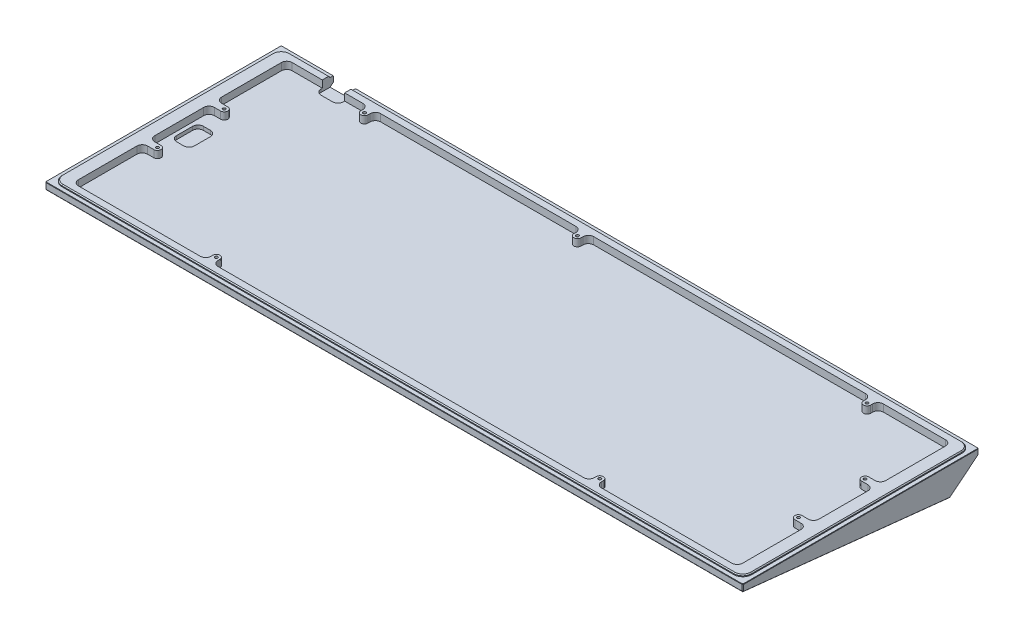
SolidWorks part; units mm, degrees
material "6061-T6 (SS)"
ref_plane "Front Plane" through (0, 0, 0) normal (0, 0, 1) x (1, 0, 0)
ref_plane "Top Plane" through (0, 0, 0) normal (0, 1, 0) x (1, 0, 0)
ref_plane "Right Plane" through (0, 0, 0) normal (1, 0, 0) x (0, 0, -1)
sketch "Sketch1" plane through (0, 0, 0) normal (0, 1, 0) x (1, 0, 0)
  line L1 (0, 0) -> (390, 0)
  line L2 (0, 0) -> (0, 132)
  line L3 (0, 132) -> (390, 132)
  line L4 (390, 0) -> (390, 132)
  dimension "D1" = 132
  dimension "D2" = 390
extrude "Boss-Extrude1" add sketch "Sketch1" along normal blind 40
sketch "Sketch2" plane through (0, 0, 0) normal (-1, 0, 0) x (0, 0, 1)
  line L0 (0, 36) -> (-115.9463, 23.8135)
  line L1 (0, 40) -> (0, 0) construction
  line L2 (-115.9463, 23.8135) -> (-132, 36.8135)
  line L3 (-132, 40) -> (-132, 0) construction
  line L4 (-132, 40) -> (0, 40) construction
  dimension "D1" = 6
  dimension "D2" = 135
  dimension "D3" = 13
  dimension "D4" = 4
extrude "Cut-Extrude1" cut sketch "Sketch2" against normal through all and the other way through all
sketch "Sketch3" plane through (0, 40, 0) normal (0, 1, 0) x (1, 0, 0)
  line L0 (390, 132) -> (0, 132) construction
  line L1 (387.75, 2.25) -> (2.25, 2.25)
  line L2 (387.75, 2.25) -> (387.75, 129.75)
  line L3 (387.75, 129.75) -> (2.25, 129.75)
  line L4 (2.25, 2.25) -> (2.25, 129.75)
  line L5 (390, 0) -> (390, 132) construction
  line L6 (0, 0) -> (390, 0) construction
  point P4 (195, 129.75)
  point P7 (195, 132)
  point P8 (387.75, 66)
  point P11 (390, 66)
  dimension "D1" = 2.25
  dimension "D2" = 2.25
extrude "Boss-Extrude2" add sketch "Sketch3" along normal blind 1
sketch "Sketch4" plane through (0, 35.6067, -3.7424) normal (0, -0.9945, 0.1045) x (1, 0, 0)
  line L0 (197.9, -58.4419) -> (195.9, -58.4419) construction
  line L1 (197.9, -66.4419) -> (195.9, -66.4419)
  line L2 (197.9, -66.4419) -> (197.9, -50.4419)
  line L3 (197.9, -50.4419) -> (195.9, -50.4419)
  line L4 (195.9, -66.4419) -> (195.9, -50.4419)
  line L5 (202.4, -58.9419) -> (200.4, -58.9419)
  line L6 (202.4, -58.9419) -> (202.4, -46.4419)
  line L7 (202.4, -46.4419) -> (200.4, -46.4419)
  line L8 (200.4, -58.9419) -> (200.4, -46.4419)
  line L9 (193.1, -58.9419) -> (191.1, -58.9419)
  line L10 (193.1, -58.9419) -> (193.1, -50.9419)
  line L11 (193.1, -50.9419) -> (191.1, -50.9419)
  line L12 (191.1, -58.9419) -> (191.1, -50.9419)
  line L13 (189.6, -58.9419) -> (187.6, -58.9419)
  line L14 (189.6, -58.9419) -> (189.6, -50.9419)
  line L15 (189.6, -50.9419) -> (187.6, -50.9419)
  line L16 (187.6, -58.9419) -> (187.6, -50.9419)
  line L17 (186.1, -58.9419) -> (184.1, -58.9419)
  line L18 (186.1, -58.9419) -> (186.1, -50.9419)
  line L19 (186.1, -50.9419) -> (184.1, -50.9419)
  line L20 (184.1, -58.9419) -> (184.1, -50.9419)
  line L21 (202.4, -58.9419) -> (187.6, -58.9419) construction
  line L22 (193.9, -62.4419) -> (197.9, -62.4419)
  line L23 (193.9, -60.4419) -> (197.9, -60.4419)
  line L24 (205.9, -50.9419) -> (203.9, -50.9419)
  line L25 (205.9, -50.9419) -> (205.9, -46.4419)
  line L26 (205.9, -46.4419) -> (203.9, -46.4419)
  line L27 (203.9, -50.9419) -> (203.9, -46.4419)
  line L28 (205.9, -50.9419) -> (184.1, -50.9419) construction
  line L29 (0, -112.822) -> (390, -112.822) construction
  circle A0 centre (201.4, -61.4419) radius 1
  circle A1 centre (193.9, -61.4419) radius 1
  circle A2 centre (196.9, -65.4419) radius 1
  circle A3 centre (196.9, -51.4419) radius 1
  circle A4 centre (201.4, -57.9419) radius 1
  circle A5 centre (201.4, -47.4419) radius 1
  circle A6 centre (204.9, -49.9419) radius 1
  circle A7 centre (204.9, -47.4419) radius 1
  circle A8 centre (192.1, -57.9419) radius 1
  circle A9 centre (192.1, -51.9419) radius 1
  circle A10 centre (188.6, -57.9419) radius 1
  circle A11 centre (188.6, -51.9419) radius 1
  circle A12 centre (185.1, -57.9419) radius 1
  circle A13 centre (185.1, -51.9419) radius 1
  point P29 (201.4, -58.9419)
  point P38 (196.9, -66.4419)
  point P63 (195, -112.822)
  point P64 (195, -50.9419)
  dimension "D10" = 2
  dimension "D12" = 2
  dimension "D1" = 16
  dimension "D2" = 2
  dimension "D3" = 2.5
  dimension "D4" = 2.8
  dimension "D5" = 1.5
  dimension "D6" = 1.5
  dimension "D7" = 8
  dimension "D8" = 0.5
  dimension "D9" = 2.5
  dimension "D11" = 12.5
  dimension "D13" = 0
  dimension "D14" = 1.5
  dimension "D15" = 4.5
  dimension "D16" = 2
  dimension "D17" = 3
  dimension "D18" = 11
  dimension "D19" = 66.3801
extrude "Cut-Extrude2" cut sketch "Sketch4" against normal blind 1 contours A5 L8 A4 L6 | A6 | A7 L27 A6 L25 | A7 | A5 | A4 | A0 | A2 | A2 L2 L22 L4 | L23 L4 L22 L2 | A1 | A1 L22 L4 L23 | A3 L4 L23 L2 | A3 | A9 | A9 L12 A8 L10 | A8 | A11 L16 A10 L14 | A10 | A11 | A13 | A13 L20 A12 L18 | A12
sketch "Sketch5" plane through (0, 41, 0) normal (0, 1, 0) x (1, 0, 0)
  line L0 (0, 132) -> (390, 132) construction
  line L1 (9.35, 125.7375) -> (380.65, 125.7375)
  line L2 (9.35, 125.7375) -> (9.35, 6.2625)
  line L3 (9.35, 6.2625) -> (380.65, 6.2625)
  line L4 (380.65, 125.7375) -> (380.65, 6.2625)
  line L6 (2.25, 129.75) -> (2.25, 2.25) construction
  line L9 (171.1875, 124.7375) -> (61.65, 124.7375) construction
  line L10 (10.85, 123.2389) -> (10.85, 89.0187) construction
  point P6 (195, 132)
  point P7 (195, 125.7375)
  point P12 (2.25, 66)
  point P13 (9.35, 66)
  dimension "D1" = 1
  dimension "D2" = 1.5
extrude "Cut-Extrude3" cut sketch "Sketch5" against normal blind 4
sketch "Sketch6" plane through (0, 37, 0) normal (0, 1, 0) x (1, 0, 0)
  line L0 (15.85, 48.95) -> (15.85, 44.95)
  line L1 (15.85, 48.95) -> (9.35, 48.95)
  line L2 (15.85, 44.95) -> (9.35, 44.95)
  line L3 (9.35, 48.95) -> (9.35, 44.95)
  line L4 (15.85, 86.288) -> (15.85, 82.288)
  line L5 (15.85, 86.288) -> (9.35, 86.288)
  line L6 (15.85, 82.288) -> (9.35, 82.288)
  line L7 (9.35, 86.288) -> (9.35, 82.288)
  line L8 (9.35, 125.7375) -> (9.35, 6.2625) construction
  line L9 (54.8875, 121.625) -> (58.8875, 121.625)
  line L10 (54.8875, 121.625) -> (54.8875, 125.7375)
  line L11 (58.8875, 121.625) -> (58.8875, 125.7375)
  line L12 (54.8875, 125.7375) -> (58.8875, 125.7375)
  line L13 (380.65, 125.7375) -> (9.35, 125.7375) construction
  line L14 (173.95, 121.625) -> (177.95, 121.625)
  line L15 (173.95, 121.625) -> (173.95, 125.7375)
  line L16 (177.95, 121.625) -> (177.95, 125.7375)
  line L17 (173.95, 125.7375) -> (177.95, 125.7375)
  line L18 (335.875, 121.625) -> (339.875, 121.625)
  line L19 (335.875, 121.625) -> (335.875, 125.7375)
  line L20 (339.875, 121.625) -> (339.875, 125.7375)
  line L21 (335.875, 125.7375) -> (339.875, 125.7375)
  line L22 (374.15, 86.288) -> (374.15, 82.288)
  line L23 (374.15, 86.288) -> (380.65, 86.288)
  line L24 (374.15, 82.288) -> (380.65, 82.288)
  line L25 (380.65, 86.288) -> (380.65, 82.288)
  line L26 (374.15, 48.95) -> (374.15, 44.95)
  line L27 (374.15, 48.95) -> (380.65, 48.95)
  line L28 (374.15, 44.95) -> (380.65, 44.95)
  line L29 (380.65, 48.95) -> (380.65, 44.95)
  line L30 (297.775, 10.275) -> (301.775, 10.275)
  line L31 (297.775, 10.275) -> (297.775, 6.2625)
  line L32 (301.775, 10.275) -> (301.775, 6.2625)
  line L33 (297.775, 6.2625) -> (301.775, 6.2625)
  line L34 (83.4625, 10.275) -> (87.4625, 10.275)
  line L35 (83.4625, 10.275) -> (83.4625, 6.2625)
  line L36 (87.4625, 10.275) -> (87.4625, 6.2625)
  line L37 (83.4625, 6.2625) -> (87.4625, 6.2625)
  line L38 (9.35, 6.2625) -> (380.65, 6.2625) construction
  line L39 (380.65, 6.2625) -> (380.65, 125.7375) construction
  circle A0 centre (15.85, 84.288) radius 2
  circle A1 centre (56.8875, 121.625) radius 2
  circle A2 centre (175.95, 121.625) radius 2
  circle A3 centre (337.875, 121.625) radius 2
  circle A4 centre (374.15, 84.288) radius 2
  circle A5 centre (374.15, 46.95) radius 2
  circle A6 centre (299.775, 10.275) radius 2
  circle A7 centre (85.4625, 10.275) radius 2
  circle A8 centre (15.85, 46.95) radius 2
  arc A9 (15.85, 82.288) -> (15.85, 86.288) centre (15.85, 84.288) ccw construction
  arc A10 (15.85, 44.95) -> (15.85, 48.95) centre (15.85, 46.95) ccw construction
  arc A11 (87.4625, 10.275) -> (83.4625, 10.275) centre (85.4625, 10.275) ccw construction
  arc A12 (301.775, 10.275) -> (297.775, 10.275) centre (299.775, 10.275) ccw construction
  arc A13 (374.15, 48.95) -> (374.15, 44.95) centre (374.15, 46.95) ccw construction
  arc A14 (374.15, 86.288) -> (374.15, 82.288) centre (374.15, 84.288) ccw construction
  arc A15 (335.875, 121.625) -> (339.875, 121.625) centre (337.875, 121.625) ccw construction
  arc A16 (173.95, 121.625) -> (177.95, 121.625) centre (175.95, 121.625) ccw construction
  arc A17 (54.8875, 121.625) -> (58.8875, 121.625) centre (56.8875, 121.625) ccw construction
  arc A18 (15.85, 82.288) -> (15.85, 86.288) centre (15.85, 84.288) ccw construction
  line M2 (9.35, 125.7375) -> (9.35, 6.2625)
  line M3 (9.35, 6.2625) -> (380.65, 6.2625)
  line M4 (380.65, 6.2625) -> (380.65, 125.7375)
  line M5 (380.65, 125.7375) -> (9.35, 125.7375)
extrude "Boss-Extrude3" add sketch "Sketch6" along normal up to surface (4 mm away) contours A0 L5 L6 M2 | L4 A0 | L4 A0 | A8 L1 L3 L2 | L0 A8 | L0 A8 | L9 A1 | L9 A1 | A1 L11 L10 M5 | L14 A2 | L14 A2 | A2 L16 L15 M5 | L18 A3 | L18 A3 | A3 L20 L19 M5 | L22 A4 | A4 L24 L23 M4 | L22 A4 | L26 A5 | L26 A5 | A5 L28 L27 M4 | A6 L31 L32 M3 | L30 A6 | L30 A6 | A7 L35 L36 M3 | L34 A7 | L34 A7 up to face at (195, 41, -66)
sketch "Sketch7" plane through (0, 0, -132) normal (0, 0, -1) x (-1, 0, 0)
  line L1 (-41.7062, 41) -> (-29.2062, 41)
  line L2 (-41.7062, 41) -> (-41.7062, 35.3)
  line L3 (-41.7062, 35.3) -> (-29.2062, 35.3)
  line L4 (-29.2062, 41) -> (-29.2062, 35.3)
  line L5 (-41.7062, 41.3) -> (-41.7062, 40.2) construction
  line L6 (-29.2062, 40.2) -> (-29.2062, 41.3) construction
  line L7 (-387.75, 41) -> (-2.25, 41) construction
  dimension "D1" = 5.7
extrude "Cut-Extrude4" cut sketch "Sketch7" against normal blind 10
sketch "Sketch8" plane through (0, 41, 0) normal (0, 1, 0) x (1, 0, 0)
  point P0 (15.85, 84.288)
  point P1 (15.85, 46.95)
  point P3 (85.4625, 10.275)
  point P5 (299.775, 10.275)
  point P7 (374.15, 46.95)
  point P9 (374.15, 84.288)
  point P11 (337.875, 121.625)
  point P13 (175.95, 121.625)
  point P15 (56.8875, 121.625)
hole_wizard "M2x0.4 Tapped Hole1" positions "3DSketch1" profile "Sketch9" tap size "M2x0.4" standard "ANSI Metric"
sketch3d "3DSketch1"
  point P0 (15.85, 41, -84.288)
  point P3 (15.85, 41, -46.95)
  point P6 (85.4625, 41, -10.275)
  point P9 (56.8875, 41, -121.625)
  point P12 (175.95, 41, -121.625)
  point P15 (299.775, 41, -10.275)
  point P18 (374.15, 41, -46.95)
  point P21 (374.15, 41, -84.288)
  point P24 (337.875, 41, -121.625)
sketch "Sketch9" plane through (15.85, 41, -84.288) normal (1, 0, 0) x (0, 0, 1)
  line L0 (0, 0) -> (0, 4.4807)
  line L1 (0, 4.4807) -> (0.8, 4)
  line L2 (0.8, 4) -> (0.8, 0)
  line L5 (0.8, 0) -> (0, 0)
  line L10 (0, 4.4807) -> (-0.8, 4) construction
  line L11 (0, -6.35) -> (0, 107.95) construction
  dimension "Tap Drill Dia." = 1.6
  dimension "Tap Drill Depth" = 4
  dimension "Drill Angle" = 118
cosmetic thread "Hole Thread1" parameters "D1"=4, "D2"=2
cosmetic thread "Hole Thread2" parameters "D1"=4, "D2"=2
cosmetic thread "Hole Thread3" parameters "D1"=4, "D2"=2
cosmetic thread "Hole Thread4" parameters "D1"=4, "D2"=2
cosmetic thread "Hole Thread5" parameters "D1"=4, "D2"=2
cosmetic thread "Hole Thread6" parameters "D1"=4, "D2"=2
cosmetic thread "Hole Thread7" parameters "D1"=4, "D2"=2
cosmetic thread "Hole Thread8" parameters "D1"=4, "D2"=2
cosmetic thread "Hole Thread9" parameters "D1"=4, "D2"=2
sketch "Sketch10" plane through (0, 37, 0) normal (0, 1, 0) x (1, 0, 0)
  line L0 (13.1562, 72.441) -> (19.6562, 72.441) construction
  line L1 (11.4062, 74.0715) -> (21.4062, 74.0715)
  line L2 (11.4062, 74.0715) -> (11.4062, 59.0715)
  line L3 (11.4062, 59.0715) -> (21.4062, 59.0715)
  line L4 (21.4062, 74.0715) -> (21.4062, 59.0715)
  line L5 (13.1562, 60.702) -> (19.6562, 60.702) construction
  line L6 (16.4062, 72.441) -> (16.4062, 60.702) construction
  point P14 (11.4062, 66.5715)
  point P15 (16.4062, 66.5715)
  point P16 (16.4062, 74.0715)
  dimension "D1" = 15
  dimension "D2" = 10
extrude "Cut-Extrude5" cut sketch "Sketch10" against normal blind 2
fillet "Fillet1" radius 3 28 edges at (41.7062, 36.15, -122) (29.2062, 36.15, -122) (380.65, 39, -6.2625) (380.65, 39, -125.7375) (9.35, 39, -125.7375) (9.35, 39, -6.2625) (83.4625, 39, -6.2625) (87.4625, 39, -6.2625) (301.775, 39, -6.2625) (297.775, 39, -6.2625) (380.65, 39, -86.288) (380.65, 39, -48.95) (380.65, 39, -44.95) (380.65, 39, -82.288) (335.875, 39, -125.7375) (339.875, 39, -125.7375) (177.95, 39, -125.7375) (173.95, 39, -125.7375) (54.8875, 39, -125.7375) (58.8875, 39, -125.7375) (9.35, 39, -82.288) (9.35, 39, -86.288) (9.35, 39, -48.95) (9.35, 39, -44.95) (21.4062, 36, -59.0715) (11.4062, 36, -59.0715) (11.4062, 36, -74.0715) (21.4062, 36, -74.0715)
fillet "Fillet2" radius 5 4 edges at (387.75, 40.5, -129.75) (387.75, 40.5, -2.25) (2.25, 40.5, -2.25) (2.25, 40.5, -129.75)
chamfer "Chamfer1" distance 0.5 angle 45 18 edges at (195, 36, 0) (390, 38, 0) (390, 29.9068, -57.9732) (390, 30.3135, -123.9732) (390, 38.4068, -132) (0, 30.3135, -123.9732) (0, 38.4068, -132) (0, 29.9068, -57.9732) (0, 38, 0) (212.2281, 41, -129.75) (386.2855, 41, -128.2855) (387.75, 41, -66) (386.2855, 41, -3.7145) (18.2281, 41, -129.75) (195, 41, -2.25) (3.7145, 41, -128.2855) (3.7145, 41, -3.7145) (2.25, 41, -66)
sketch "Sketch11" plane through (0, 35.6067, -3.7424) normal (0, -0.9945, 0.1045) x (1, 0, 0)
  line L0 (0.5, -112.822) -> (389.5, -112.822) construction
  line L1 (389.5, -112.822) -> (389.5, 3.263) construction
  line L2 (0, -112.6149) -> (0, 3.3128) construction
  line L3 (389.5, 3.263) -> (0.5, 3.263) construction
  circle A0 centre (379.5, -102.822) radius 5.5
  circle A1 centre (379.5, -6.737) radius 5.5
  circle A2 centre (10, -102.822) radius 5.5
  circle A3 centre (10, -6.737) radius 5.5
  dimension "D1" = 11
  dimension "D2" = 10
  dimension "D3" = 10
  dimension "D4" = 10
  dimension "D5" = 10
extrude "Cut-Extrude6" cut sketch "Sketch11" against normal blind 0.1
chamfer "Chamfer2" distance 0.2 angle 45 9 edges at (215.6031, 40, -132) (389.75, 40, -131.75) (390, 40, -66) (389.75, 40, -0.25) (195, 40, 0) (0.25, 40, -0.25) (0, 40, -66) (0.25, 40, -131.75) (14.8531, 40, -132)
